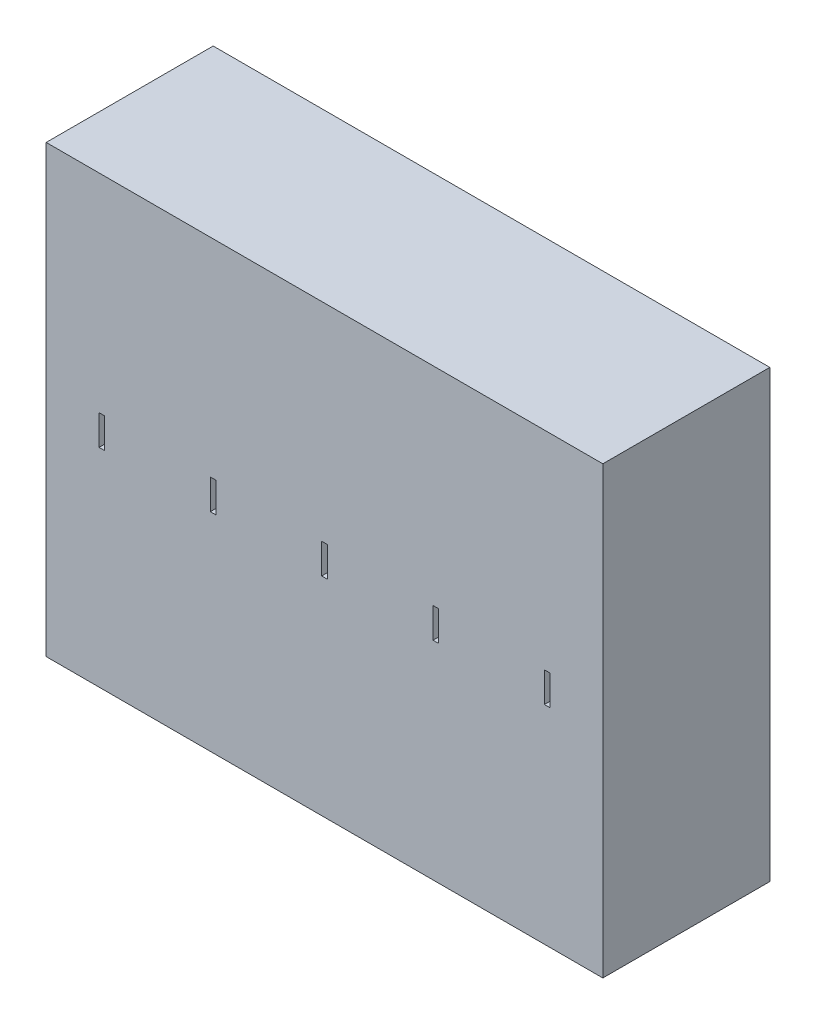
SolidWorks part; units mm, degrees
ref_plane "Ebene vorne" through (0, 0, 0) normal (0, 0, 1) x (1, 0, 0)
ref_plane "Ebene oben" through (0, 0, 0) normal (0, 1, 0) x (1, 0, 0)
ref_plane "Ebene rechts" through (0, 0, 0) normal (1, 0, 0) x (0, 0, -1)
sketch "Skizze1" plane through (0, 0, 0) normal (0, 0, 1) x (1, 0, 0)
  line L1 (-2.5, -2) -> (2.5, -2)
  line L2 (-2.5, -2) -> (-2.5, 2)
  line L3 (-2.5, 2) -> (2.5, 2)
  line L4 (2.5, -2) -> (2.5, 2)
  line L5 (-2.5, -2) -> (2.5, 2) construction
  line L6 (-2.5, 2) -> (2.5, -2) construction
  point P1 (0, 0)
  dimension "D1" = 5
  dimension "D2" = 4
extrude "Aufsatz-Linear austragen1" add sketch "Skizze1" along normal blind 1.5
sketch "Skizze2" plane through (0, 0, 1.5) normal (0, 0, 1) x (1, 0, 0)
  line L0 (-2.5, 2) -> (-2.5, -2) construction
  line L1 (-2.025, 0.135) -> (-1.975, 0.135)
  line L2 (-2.025, 0.135) -> (-2.025, -0.135)
  line L3 (-2.025, -0.135) -> (-1.975, -0.135)
  line L4 (-1.975, 0.135) -> (-1.975, -0.135)
  line L5 (-2.025, 0.135) -> (-1.975, -0.135) construction
  line L6 (-2.025, -0.135) -> (-1.975, 0.135) construction
  line L11 (2.5, 2) -> (-2.5, 2) construction
  point P0 (-2, 0)
  point P5 (-2.5, 0)
  point P6 (0, 2)
  point P9 (-0.4769, 0.075)
  point P12 (0, 0)
  dimension "D1" = 0.5
  dimension "D2" = 0.27
  dimension "D3" = 0.05
extrude "Schnitt-Linear austragen1" cut sketch "Skizze2" against normal blind 0.2
pattern_linear "Lineares Muster1" count 5 spacing 1 along (1, 0, 0) of "Schnitt-Linear austragen1"
sketch "Skizze4" plane through (0, 0, 1.3) normal (0, 0, 1) x (1, 0, 0)
  line L8 (-1.985, -0.125) -> (-1.985, 0.125)
  line L9 (-1.985, 0.125) -> (-2.015, 0.125)
  line L10 (-2.015, 0.125) -> (-2.015, -0.125)
  line L11 (-2.015, -0.125) -> (-1.985, -0.125)
  line L12 (-1.985, -0.125) -> (-1.985, 0.125)
  line L13 (-1.985, 0.125) -> (-2.015, 0.125)
  line L14 (-2.015, 0.125) -> (-2.015, -0.125)
  line L15 (-2.015, -0.125) -> (-1.985, -0.125)
  dimension "D1" = 0.01
sketch "Skizze5" plane through (0, 0, 1.3) normal (0, 0, 1) x (1, 0, 0)
  line L2 (-0.965, -0.135) -> (-0.965, 0.135)
  line L3 (-0.965, -0.135) -> (-0.965, 0.135)
  line L11 (-0.985, -0.125) -> (-0.985, 0.125)
  line L12 (-0.985, 0.125) -> (-1.015, 0.125)
  line L13 (-1.015, 0.125) -> (-1.015, -0.125)
  line L14 (-1.015, -0.125) -> (-0.985, -0.125)
  line L15 (-0.985, -0.125) -> (-0.985, 0.125)
  line L16 (-0.985, 0.125) -> (-1.015, 0.125)
  line L17 (-1.015, 0.125) -> (-1.015, -0.125)
  line L18 (-1.015, -0.125) -> (-0.985, -0.125)
  line L23 (0.015, -0.125) -> (0.015, 0.125)
  line L24 (0.015, 0.125) -> (-0.015, 0.125)
  line L25 (-0.015, 0.125) -> (-0.015, -0.125)
  line L26 (-0.015, -0.125) -> (0.015, -0.125)
  line L27 (0.015, -0.125) -> (0.015, 0.125)
  line L28 (0.015, 0.125) -> (-0.015, 0.125)
  line L29 (-0.015, 0.125) -> (-0.015, -0.125)
  line L30 (-0.015, -0.125) -> (0.015, -0.125)
  dimension "D1" = 0.01
  dimension "D2" = 0.01
  dimension "D3" = 0.01
ref_point "SWASI_Filter_Spawn_1"
ref_point "SWASI_Filter_Spawn_2"
ref_point "SWASI_Filter_Spawn_3"
